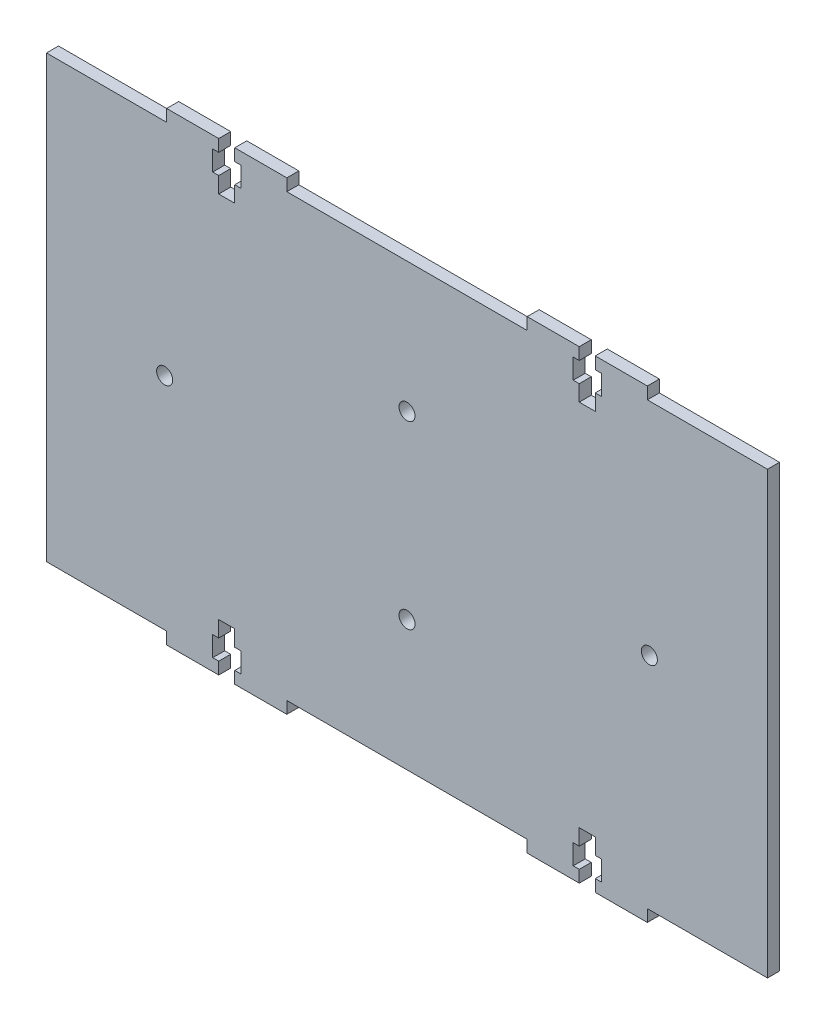
SolidWorks part; units mm, degrees
ref_plane "前视基准面" through (0, 0, 0) normal (0, 0, 1) x (1, 0, 0)
ref_plane "上视基准面" through (0, 0, 0) normal (0, 1, 0) x (1, 0, 0)
ref_plane "右视基准面" through (0, 0, 0) normal (1, 0, 0) x (0, 0, -1)
sketch "草图1" plane through (0, 0, 0) normal (0, 0, 1) x (1, 0, 0)
  line L0 (90, 0) -> (90, -110)
  line L1 (0, 0) -> (180, 0)
  line L2 (0, 0) -> (0, -110)
  line L3 (0, -110) -> (180, -110)
  line L4 (180, 0) -> (180, -110)
  line L5 (0, -55) -> (180, -55)
  line L6 (137, -9) -> (133, -9)
  line L7 (30, 0) -> (60, 0)
  line L8 (30, 0) -> (30, 3)
  line L9 (30, 3) -> (60, 3)
  line L10 (60, 0) -> (60, 3)
  line L11 (43, 3) -> (47, 3)
  line L12 (43, 3) -> (43, -9)
  line L13 (43, -9) -> (47, -9)
  line L14 (47, 3) -> (47, -9)
  line L15 (41.5, 0) -> (48.5, 0)
  line L16 (41.5, 0) -> (41.5, -5)
  line L17 (41.5, -5) -> (48.5, -5)
  line L18 (48.5, 0) -> (48.5, -5)
  line L19 (133, 3) -> (133, -9)
  line L20 (137, 3) -> (133, 3)
  line L21 (137, 3) -> (137, -9)
  line L22 (138.5, -5) -> (131.5, -5)
  line L23 (131.5, 0) -> (131.5, -5)
  line L24 (138.5, 0) -> (131.5, 0)
  line L25 (138.5, 0) -> (138.5, -5)
  line L26 (150, 3) -> (120, 3)
  line L27 (120, 0) -> (120, 3)
  line L28 (150, 0) -> (120, 0)
  line L29 (150, 0) -> (150, 3)
  line L30 (30, -113) -> (60, -113)
  line L31 (60, -110) -> (60, -113)
  line L32 (30, -110) -> (60, -110)
  line L33 (30, -110) -> (30, -113)
  line L34 (41.5, -105) -> (48.5, -105)
  line L35 (48.5, -110) -> (48.5, -105)
  line L36 (41.5, -110) -> (48.5, -110)
  line L37 (41.5, -110) -> (41.5, -105)
  line L38 (43, -101) -> (47, -101)
  line L39 (47, -113) -> (47, -101)
  line L40 (43, -113) -> (47, -113)
  line L41 (43, -113) -> (43, -101)
  line L42 (138.5, -110) -> (138.5, -105)
  line L43 (138.5, -110) -> (131.5, -110)
  line L44 (131.5, -110) -> (131.5, -105)
  line L45 (138.5, -105) -> (131.5, -105)
  line L46 (137, -113) -> (137, -101)
  line L47 (137, -113) -> (133, -113)
  line L48 (133, -113) -> (133, -101)
  line L49 (137, -101) -> (133, -101)
  line L50 (150, -110) -> (150, -113)
  line L51 (150, -110) -> (120, -110)
  line L52 (120, -110) -> (120, -113)
  line L53 (150, -113) -> (120, -113)
  dimension "D1" = 180
  dimension "D2" = 110
  dimension "D3" = 30
  dimension "D4" = 3
  dimension "D5" = 30
  dimension "D6" = 4
  dimension "D7" = 13
  dimension "D8" = 12
  dimension "D9" = 7
  dimension "D10" = 5
  dimension "D11" = 1.5
extrude "凸台-拉伸1" add sketch "草图1" along normal blind 3 contours L7 L18 L17 L14 L13 L12 L16 L1 L2 L5 L0 | L1 L25 L22 L21 L6 L19 L23 L0 L5 L4 | L49 L46 L45 L42 L3 L4 L5 L0 L44 L48 | L34 L41 L38 L39 L35 L32 L3 L0 L5 L2 L37 | L27 L1 L19 L26 | L1 L29 L26 L21 | L12 L9 L8 L1 L7 | L9 L14 L1 L7 L10 | L39 L30 L31 L32 L36 | L30 L41 L32 L3 L33 | L53 L50 L3 L43 L46 | L53 L48 L3 L52
sketch "草图2" plane through (0, 0, 3) normal (0, 0, 1) x (1, 0, 0)
  line L0 (90, 0) -> (90, -110)
  line L1 (60, 0) -> (120, 0) construction
  line L2 (60, -110) -> (120, -110) construction
  line L3 (0, -55) -> (180, -55)
  line L4 (0, 0) -> (0, -110) construction
  line L5 (180, 0) -> (180, -110) construction
  line L6 (0, 0) -> (30, 0) construction
  line L7 (29.5, -32.5) -> (150.5, -32.5)
  line L8 (29.5, -32.5) -> (29.5, -77.5)
  line L9 (29.5, -77.5) -> (150.5, -77.5)
  line L10 (150.5, -32.5) -> (150.5, -77.5)
  line L11 (29.5, -32.5) -> (150.5, -77.5) construction
  line L12 (29.5, -77.5) -> (150.5, -32.5) construction
  line L13 (0, -110) -> (30, -110) construction
  circle A0 centre (29.5, -55) radius 2
  circle A1 centre (150.5, -55) radius 2
  circle A2 centre (90, -77.5) radius 2
  circle A3 centre (90, -32.5) radius 2
  point P12 (90, -55)
  dimension "D3" = 4
  dimension "D4" = 4
  dimension "D1" = 121
  dimension "D2" = 45
extrude "切除-拉伸1" cut sketch "草图2" against normal through all contours L3 A0 L8 | L8 A0 L3 | L3 A0 L8 | L8 A0 L3 | L9 A2 L0 | L0 A2 L9 | L9 A2 L0 | L0 A2 L9 | A3 L0 L7 | A3 L0 L7 | A3 L7 L0 | A3 L7 L0 | A1 L3 L10 | A1 L10 L3 | A1 L3 L10 | A1 L10 L3
